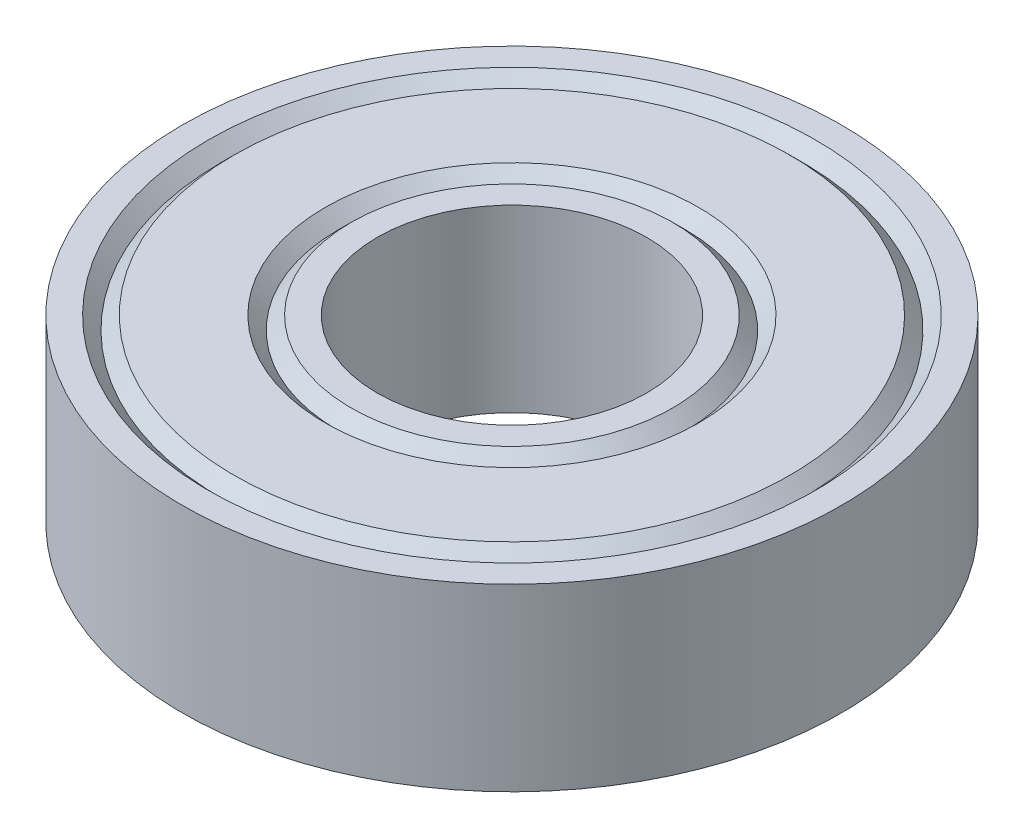
SolidWorks part; units mm, degrees
ref_plane "Front Plane" through (0, 0, 0) normal (0, 0, 1) x (1, 0, 0)
ref_plane "Top Plane" through (0, 0, 0) normal (0, 1, 0) x (1, 0, 0)
ref_plane "Right Plane" through (0, 0, 0) normal (1, 0, 0) x (0, 0, -1)
sketch "Sketch1" plane through (0, 0, 0) normal (0, 0, 1) x (1, 0, 0)
  line L0 (0, 3) -> (0, -3) construction
  line L1 (-4.5, 3) -> (-5.3667, 3)
  line L2 (-4.5, 3) -> (-4.5, -3)
  line L3 (-4.5, -3) -> (-5.3667, -3)
  line L4 (-11, 3) -> (-11, -3)
  line L5 (-10.1333, 3) -> (-9.7, 2.5667)
  line L6 (-9.7, 2.5667) -> (-9.2667, 3)
  line L7 (-6.2333, 3) -> (-5.8, 2.5667)
  line L8 (-5.8, 2.5667) -> (-5.3667, 3)
  line L9 (-10.1333, -3) -> (-9.7, -2.5667)
  line L10 (-9.7, -2.5667) -> (-9.2667, -3)
  line L11 (-6.2333, -3) -> (-5.8, -2.5667)
  line L12 (-5.8, -2.5667) -> (-5.3667, -3)
  line L13 (-6.2333, -3) -> (-9.2667, -3)
  line L14 (-10.1333, -3) -> (-11, -3)
  line L15 (-10.1333, 3) -> (-11, 3)
  line L16 (-6.2333, 3) -> (-9.2667, 3)
  line L17 (-9.7, 2.5667) -> (-5.8, 2.5667) construction
  line L18 (-9.7, 2.5667) -> (-9.7, -2.5667) construction
  line L19 (-5.8, -2.5667) -> (-9.7, -2.5667) construction
  line L20 (-5.8, 2.5667) -> (-5.8, -2.5667) construction
  line L21 (-9.7, 0) -> (-8.4, 0) construction
  line L22 (-5.3667, 3) -> (-6.2333, 3) construction
  line L23 (-8.4, 0) -> (-7.1, 0) construction
  line L24 (-9.7, 0) -> (-11, 0) construction
  line L25 (-7.1, 0) -> (-5.8, 0) construction
  line L26 (-5.8, 0) -> (-4.5, 0) construction
  dimension "D1" = 6
  dimension "D2" = 9
  dimension "D3" = 22
revolve "Revolve1" add sketch "Sketch1" angle 360 about L0
